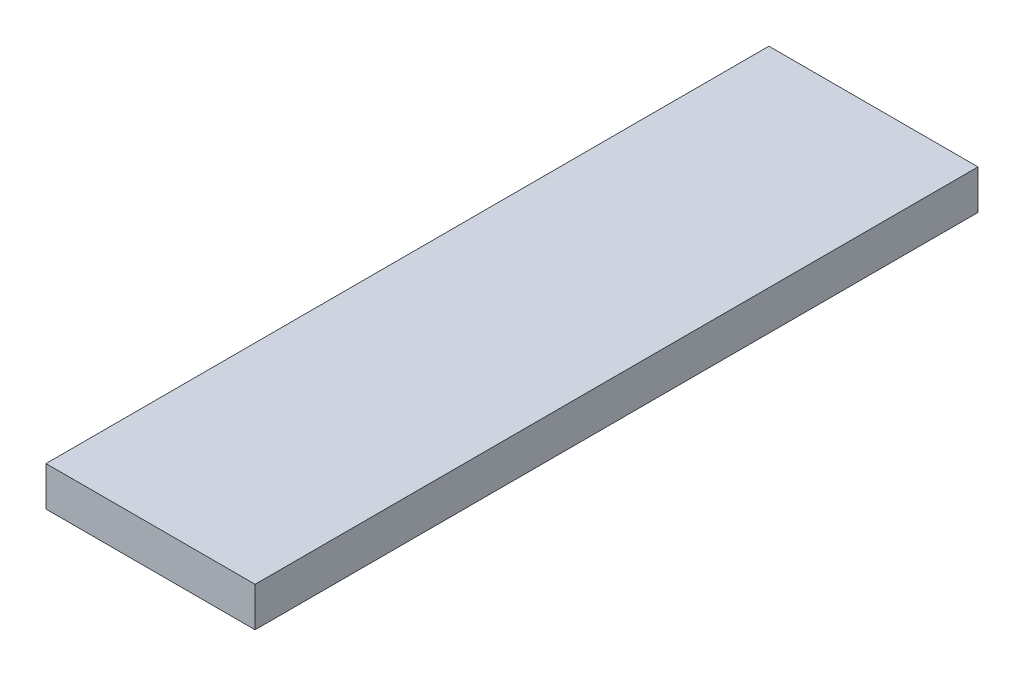
SolidWorks part; units mm, degrees
ref_plane "Front Plane" through (0, 0, 0) normal (0, 0, 1) x (1, 0, 0)
ref_plane "Top Plane" through (0, 0, 0) normal (0, 1, 0) x (1, 0, 0)
ref_plane "Right Plane" through (0, 0, 0) normal (1, 0, 0) x (0, 0, -1)
sketch "Sketch2" plane through (0, 0, 0) normal (0, 1, 0) x (1, 0, 0)
  line L1 (0, 0) -> (24.384, 0)
  line L2 (0, 0) -> (0, 84.3)
  line L3 (0, 84.3) -> (24.384, 84.3)
  line L4 (24.384, 0) -> (24.384, 84.3)
  line L5 (0, 0) -> (24.384, 84.3) construction
  line L6 (0, 84.3) -> (24.384, 0) construction
  point P4 (12.192, 42.15)
  dimension "D1" = 24.384
  dimension "D2" = 84.3
extrude "Boss-Extrude1" add sketch "Sketch2" along normal blind 4.6
equation "\"MDF\"= 4.8mm"
equation "\"Foamcore\"= 4.6mm"
equation "\"GMaterial\"= \"MDF\""
equation "\"PCB\" = 1.6mm"
equation "\"BaseWidth\" = 10in"
equation "\"SkidLength\" = 1in"
equation "\"SkidClearance\" = 0.4in"
equation "\"MotorMountLength\" = 2in"
equation "\"MotorMountWidth\" = \"GMaterial\""
equation "\"MotorMountHeight\" = 2.25in"
equation "\"UnoStackWidth\" = 77.4mm"
equation "\"UnoStackLength\" = 79.8mm"
equation "\"UnoStackHeight\" = 34.2mm"
equation "\"TallHexRiserHeight\" = 22.2mm"
equation "\"PingPongBallSize\" = 40mm"
equation "\"BarrelLength\" = 9in"
equation "\"BarrelSize\" = \"PingPongBallSize\""
equation "\"PlatformLength\" = 4in"
equation "\"PlatformWidth\" = 6in"
equation "\"WheelDiameter\"=2.99213"
equation "\"ServoMountHeight\"=2.49223"
equation "\"ServoGearHeight\" = 0.95330261in"
equation "\"ServoMountLength\"= 1.53774"
equation "\"PivotHoleRadius\"= 0.616358"
equation "\"PlatformMountHeight\" = 3.19"
equation "\"TensionOffSet\"= .3mm"
equation "\"MotorMountWedge\"=0.333333"
equation "\"LaserCutterOffset\"= .3mm"
equation "\"BumperWidth\"=11"
equation "\"PitcherWheelCompression\" = 2.5mm"
equation "\"PitchingWheelWidth\" = 26.2mm"
equation "\"PitchingWheelDiameter\" = 65.5mm"
equation "\"PitchingWheelMountOffset\" = 8.4mm"
equation "\"PitchingWheelInnerDiameter\" = 45.5mm"
equation "\"PitchingWheelBoltShoulder\" = 4.5mm"
equation "\"BrassCouplingLength\" = 18mm"
equation "\"PitchingMotorHeight\" = 57.0mm"
equation "\"PitchingMotorShaftTopHeight\" = \"PitchingMotorHeight\" - 44.1mm"
equation "\"PitchingMotorBodyHeight\" = 38mm"
equation "\"PitchingMotorTopShoulderHeight\" = 40.6mm - \"PitchingMotorBodyHeight\" "
equation "\"PitchingMotorBottomShoulderHeight\" = 40.2mm - \"PitchingMotorBodyHeight\""
equation "\"PitchingMotorBottomShaftHeight\" = \"PitchingMotorHeight\" - \"PitchingMotorShaftTopHeight\" - \"PitchingMotorTopShoulderHeight\" - \"PitchingMotorBodyHeight\" - \"PitchingMotorBottomShoulderHeight\""
equation "\"PitchingMotorShaftDiameter\" = 2.2mm"
equation "\"PitchingMotorBodyDiameter\" = 27.4mm"
equation "\"PitchingMotorTopShoulderDiameter\" = 9.8mm"
equation "\"PitchingMotorBottomShoulderDiameter\" = 9.8mm"
equation "\"BrassCouplingHexSize\" = 12mm"
equation "\"BrassCouplingBoreSize\" = 3.17mm"
equation "\"PitchingMotorMountingHoleDistance\" = 16mm"
equation "\"Acrylic\" = 4.4mm"
equation "\"PitchingMotorDistance\" = \"PitchingWheelDiameter\" + \"PingPongBallSize\" - \"PitcherWheelCompression\"*2"
equation "\"PitchingMotorPlatformOffset\"=1"
equation "\"ServoPlatformOffset\"=1.64173"
equation "\"BallBearingDiameter\" = 22mm"
equation "\"BallBearingWidth\" = 9mm"
equation "\"BallBearingHexShoulder\" = 9mm - 5.9mm"
equation "\"BallBearingHexSize\" = .36in"
equation "\"PlatformMountFootLength\"=0.857143"
equation "\"WheelWidth\"= 26mm"
equation "\"ServoMountReductionBackHeight\"=2.25"
equation "\"PlatformBottomWidthThird\" =  0.857143in"
equation "\"PlatformMountBackReductionHeight\"= 2.5in"
equation "\"PlatformMountBackReductionWidth\"= 3/7in"
equation "\"PlatformMountFrontReductionWidth\" =  1.46226in"
equation "\"PlatformMountFrontReductionHeight\" = 2.5in"
equation "\"HopperLongWallLength\" = 8.646in"
equation "\"HopperShortWallLength\" = 0.9571in"
equation "\"D1@Boss-Extrude1\"=\"Foamcore\""
equation "\"HopperHeight\" = 3.50in - \"Foamcore\""
equation "\"D2@Sketch2\"=\"HopperHeight\""
